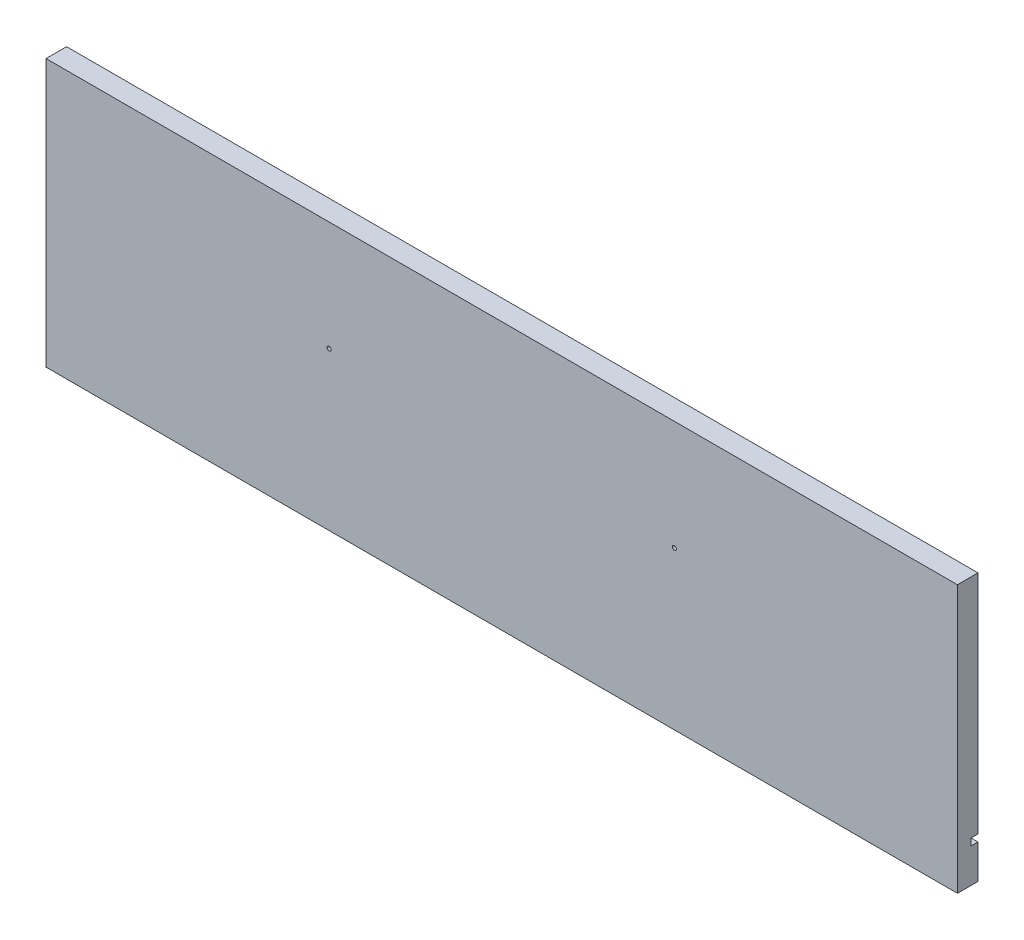
SolidWorks part; units mm, degrees
ref_plane "Front" through (0, 0, 0) normal (0, 0, 1) x (1, 0, 0)
ref_plane "Top" through (0, 0, 0) normal (0, 1, 0) x (1, 0, 0)
ref_plane "Right" through (0, 0, 0) normal (1, 0, 0) x (0, 0, -1)
sketch "Sketch1" plane through (0, 0, 0) normal (0, 0, 1) x (1, 0, 0)
  line L1 (-332.5, 0) -> (332.5, 0)
  line L2 (-332.5, 0) -> (-332.5, 195)
  line L3 (-332.5, 195) -> (332.5, 195)
  line L4 (332.5, 0) -> (332.5, 195)
  point P4 (0, 0)
  dimension "D1" = 665
  dimension "D2" = 195
extrude "Base-Extrude" add sketch "Sketch1" against normal blind 15
sketch "Sketch2" plane through (332.5, 0, 0) normal (1, 0, 0) x (0, 0, -1)
  line L0 (15, 0) -> (15, 195) construction
  line L1 (15, 25) -> (10, 25)
  line L2 (15, 25) -> (15, 30)
  line L3 (15, 30) -> (10, 30)
  line L4 (10, 25) -> (10, 30)
  line L5 (15, 0) -> (0, 0) construction
  dimension "D1" = 25
  dimension "D2" = 5
  dimension "D3" = 5
extrude "Cut-Extrude1" cut sketch "Sketch2" against normal through all
hole_wizard "M3.0 (3.000000) Diameter Hole1" positions "Sketch7" profile "Sketch8" hole size "M3.0" standard "Ansi Metric" end condition through all
sketch "Sketch7" plane through (0, 0, 0) normal (0, 0, 1) x (1, 0, 0)
  line L1 (0, 0) -> (0, 195) construction
  line L2 (332.5, 115) -> (-332.5, 115)
  line L3 (332.5, 115) -> (-332.5, 115) construction
  line L4 (332.5, 195) -> (-332.5, 195) construction
  line L5 (-332.5, 195) -> (-332.5, 0) construction
  point P0 (-126, 115)
  point P8 (126, 115)
  dimension "D2" = 206.5
  dimension "D3" = 252
  dimension "D1" = 80
sketch "Sketch8" plane through (-126, 115, 0) normal (1, 0, 0) x (0, -1, 0)
  line L0 (0, 0) -> (0, 15)
  line L1 (0, 15) -> (1.5, 15)
  line L2 (1.5, 15) -> (1.5, 0)
  line L5 (1.5, 0) -> (0, 0)
  line L11 (0, -6.35) -> (0, 107.95) construction
  dimension "Thru Hole Dia." = 3
  dimension "Thru Hole Depth" = 15
hole_wizard "M3.0 (3.000000) Diameter Hole2" positions "Sketch10" profile "Sketch9" hole size "M3.0" standard "Ansi Metric"
sketch "Sketch10" plane through (0, 0, -15) normal (0, 0, -1) x (-1, 0, 0)
  point P1 (-325, 135)
  point P2 (-325, 45)
  point P4 (325, 135)
  point P6 (325, 45)
sketch "Sketch9" plane through (325, 135, -15) normal (1, 0, 0) x (0, 1, 0)
  line L0 (0, 0) -> (0, 10.9013)
  line L1 (0, 10.9013) -> (1.5, 10)
  line L2 (1.5, 10) -> (1.5, 0)
  line L5 (1.5, 0) -> (0, 0)
  line L10 (0, 10.9013) -> (-1.5, 10) construction
  line L11 (0, -6.35) -> (0, 107.95) construction
  dimension "Hole Dia." = 3
  dimension "Hole Depth" = 10
  dimension "Drill Angle" = 118
